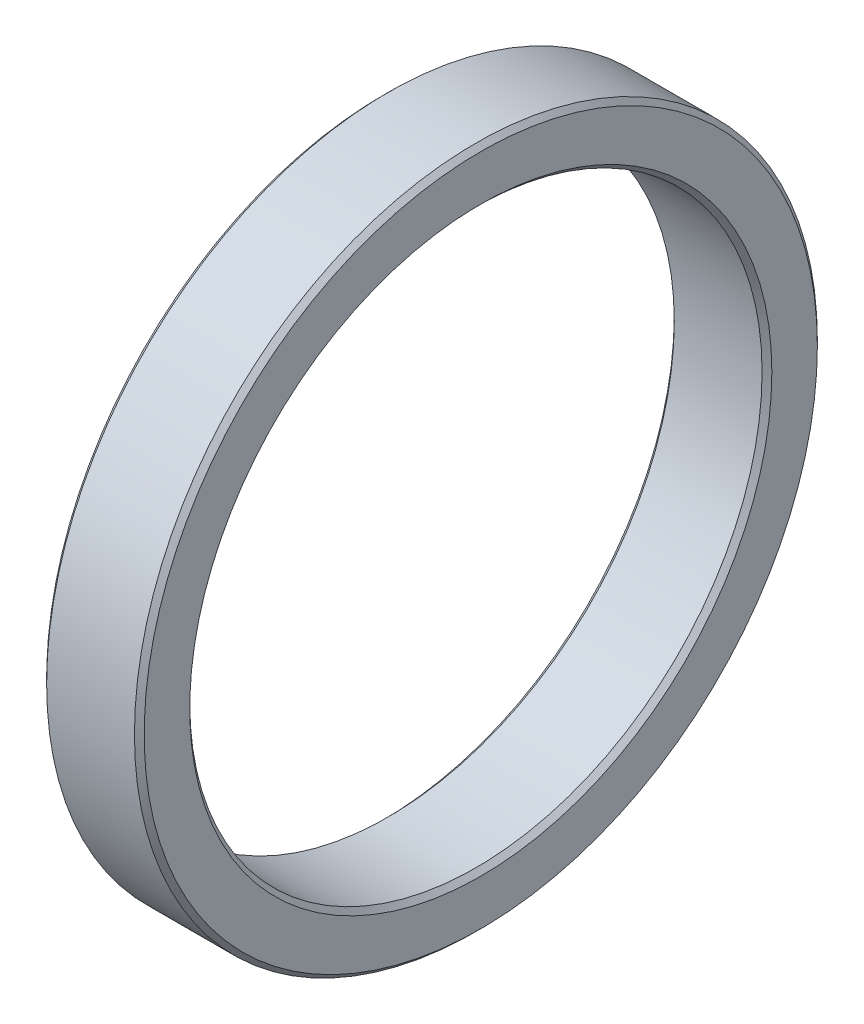
SolidWorks part; units mm, degrees
ref_plane "前视基准面" through (0, 0, 0) normal (0, 0, 1) x (1, 0, 0)
ref_plane "上视基准面" through (0, 0, 0) normal (0, 1, 0) x (1, 0, 0)
ref_plane "右视基准面" through (0, 0, 0) normal (1, 0, 0) x (0, 0, -1)
other "Configuration Table"
sketch "草图1" plane through (0, 0, 0) normal (1, 0, 0) x (0, 0, -1)
  circle A0 centre (0, 0) radius 17.6
  circle A1 centre (0, 0) radius 21
  dimension "D1" = 35.2
  dimension "D2" = 42
extrude "凸台-拉伸1" add sketch "草图1" along normal blind 6
chamfer "倒角1" distance 0.3 angle 45 4 edges at (0, 0, -17.6) (6, 0, -17.6) (0, 0, -21) (6, 0, -21)
